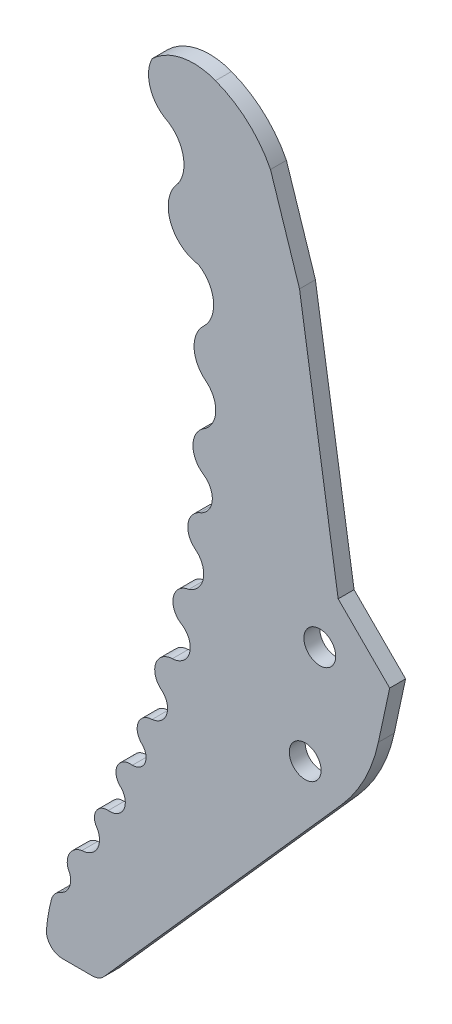
SolidWorks part; units mm, degrees
ref_plane "Front Plane" through (0, 0, 0) normal (0, 0, 1) x (1, 0, 0)
ref_plane "Top Plane" through (0, 0, 0) normal (0, 1, 0) x (1, 0, 0)
ref_plane "Right Plane" through (0, 0, 0) normal (1, 0, 0) x (0, 0, -1)
sketch "Sketch1" plane through (0, 0, 0) normal (0, 0, 1) x (1, 0, 0)
  line L0 (10.1218, 0) -> (2.5, 0) construction
  line L16 (5.147, -5.6126) -> (7.4417, -13.2)
  line L17 (16.8006, -3.4123) -> (24.6469, -23.8519)
  line L18 (25.0875, -29.5388) -> (22.1552, -43.1693)
  line L19 (19.858, -47.7041) -> (4.914, -64.542)
  line L20 (4.1661, -64.8782) -> (2.2859, -64.8782)
  line L21 (2.6676, 0.8279) -> (1.1408, 1.0183)
  line L22 (2.5, 0) -> (1.25, 0) construction
  line L26 (10.1218, 0) -> (-0.1303, -1.4408) construction
  line L27 (2.7011, -1.0876) -> (1.1818, -1.3311)
  line L28 (3.2523, -3.0101) -> (1.8349, -3.6086)
  line L34 (15.628, -20.9466) -> (13.7664, -16.0577) construction
  line L35 (14.5003, -21.376) -> (12.6387, -16.4871)
  line L36 (16.7556, -20.5172) -> (14.8941, -15.6283)
  line L37 (22.6069, -26.4997) -> (42.7977, -26.4997) construction
  line L38 (17.5548, -46.4997) -> (44.5231, -46.4997) construction
  line L41 (1.25, -4.8178) -> (1.25, -68.9399) construction
  line L42 (3.1515, 2.7685) -> (1.714, 3.3172)
  line L43 (4.0802, 4.4441) -> (2.8532, 5.3724)
  line L44 (5.4696, 5.8828) -> (4.499, 7.0767)
  line L45 (7.1117, 6.8695) -> (6.5132, 8.2869)
  line L46 (9.0342, 7.4207) -> (8.7907, 8.94)
  line L47 (10.9497, 7.4542) -> (11.1401, 8.981)
  line L48 (12.8903, 6.9703) -> (13.439, 8.4078)
  line L49 (14.5659, 6.0415) -> (15.4942, 7.2686)
  line L50 (16.0045, 4.6522) -> (17.1984, 5.6228)
  line L51 (16.9912, 3.0101) -> (18.4087, 3.6086)
  line L52 (17.5425, 1.0876) -> (19.0617, 1.3311)
  line L53 (17.5759, -0.8279) -> (19.1027, -1.0183)
  line L54 (17.0921, -2.7685) -> (18.5296, -3.3172)
  line L63 (4.239, -4.6522) -> (3.0451, -5.6228) [skipped]
  line L64 (5.6777, -6.0415) -> (5.3912, -6.4202) [skipped]
  line L65 (7.3533, -6.9703) -> (6.8046, -8.4078) [skipped]
  line L66 (9.2939, -7.4542) -> (9.1035, -8.981) [skipped]
  line L67 (11.2093, -7.4207) -> (11.4529, -8.94) [skipped]
  line L68 (13.6719, -8.1484) -> (13.7304, -8.2869) [skipped]
  line L69 (14.774, -5.8828) -> (15.6913, -7.0112) [skipped]
  line L70 (16.1633, -4.4441) -> (17.3904, -5.3724) [skipped]
  arc A13 (7.1115, -14.2685) -> (9.6978, -21.1131) centre (9.5249, -17.2675) ccw
  arc A16 (1.1818, -1.3311) -> (1.8349, -3.6086) centre (1.5311, -2.4634) ccw
  arc A23 (10.7326, -21.97) -> (10.8477, -22.8183) centre (-44.6411, -29.9177) cw
  arc A24 (1.6015, -62) -> (1.2897, -63.791) centre (11.9543, -64.725) ccw
  arc A25 (4.914, -64.542) -> (4.1661, -64.8782) centre (4.1661, -63.8782) cw
  arc A26 (2.2859, -64.8782) -> (1.2897, -63.791) centre (2.2859, -63.8782) cw
  arc A27 (22.1552, -43.1693) -> (19.858, -47.7041) centre (12.3789, -41.0662) cw
  arc A28 (24.6469, -23.8519) -> (25.0875, -29.5388) centre (15.3111, -27.4357) cw
  circle A30 centre (10.1218, 0) radius 1
  circle A31 centre (15.628, -9.2603) radius 2.25
  circle A32 centre (9.1218, -17.5263) radius 0.9981
  arc A33 (14.5003, -21.376) -> (16.7556, -20.5172) centre (15.628, -20.9466) ccw
  arc A34 (14.8941, -15.6283) -> (12.6387, -16.4871) centre (13.7664, -16.0577) ccw
  circle A35 centre (22.6069, -26.4997) radius 1
  circle A36 centre (22.6069, -33.1664) radius 1
  circle A37 centre (18.4742, -39.833) radius 1
  circle A38 centre (17.5548, -46.4997) radius 1
  arc A39 (3.5195, -58.3776) -> (4.478, -56.6894) centre (3.4947, -57.2474) ccw
  arc A40 (4.478, -56.6894) -> (5.1728, -55.3731) centre (5.1184, -56.1859) cw
  arc A41 (5.1728, -55.3731) -> (5.9791, -53.7296) centre (5.2695, -54.401) ccw
  arc A42 (5.9791, -53.7296) -> (6.6933, -52.1481) centre (6.5575, -53.0388) cw
  arc A43 (6.6933, -52.1481) -> (7.2971, -50.6981) centre (6.7052, -51.3023) ccw
  arc A44 (7.2971, -50.6981) -> (7.932, -49.0351) centre (7.9512, -49.9951) cw
  arc A45 (7.932, -49.0351) -> (8.5712, -47.1764) centre (7.8216, -47.9579) ccw
  arc A46 (8.5712, -47.1764) -> (9.2023, -45.0931) centre (9.247, -46.2439) cw
  arc A47 (9.2023, -45.0931) -> (9.7684, -42.9183) centre (9.1568, -43.9202) ccw
  arc A48 (9.7684, -42.9183) -> (10.2303, -40.8052) centre (10.39, -41.9471) cw
  arc A49 (10.2303, -40.8052) -> (10.6508, -38.4154) centre (9.7964, -39.497) ccw
  arc A50 (10.6508, -38.4154) -> (10.9372, -36.2787) centre (11.4277, -37.432) cw
  arc A51 (10.9372, -36.2787) -> (11.1453, -34.0756) centre (10.4704, -35.1232) ccw
  arc A52 (11.1453, -34.0756) -> (11.277, -31.5211) centre (12.0035, -32.8392) cw
  arc A53 (11.277, -31.5211) -> (11.2908, -28.902) centre (10.2837, -30.2063) ccw
  arc A54 (11.2908, -28.902) -> (11.1632, -26.0077) centre (12.4931, -27.399) cw
  arc A55 (11.1632, -26.0077) -> (10.8477, -22.8183) centre (9.7776, -24.5344) ccw
  arc A57 (9.6978, -21.1131) -> (10.7326, -21.97) centre (9.7427, -22.112) cw
  arc A58 (7.4417, -13.2) -> (7.1115, -14.2685) centre (6.4845, -13.4895) cw
  arc A59 (3.5195, -58.3776) -> (2.639, -59.7833) centre (3.7042, -59.4719) ccw
  arc A60 (2.639, -59.7833) -> (2.1678, -61.3383) centre (1.7398, -60.3597) cw
  arc A61 (2.1678, -61.3383) -> (1.6015, -62) centre (2.5686, -62.2545) ccw
  arc A70 (16.8006, -3.4123) -> (17.0921, -2.7685) centre (10.1218, 0) ccw
  arc A71 (1.714, 3.3172) -> (1.1408, 1.0183) centre (1.4503, 2.162) ccw
  arc A72 (4.499, 7.0767) -> (2.8532, 5.3724) centre (3.6931, 6.2081) ccw
  arc A73 (8.7907, 8.94) -> (6.5132, 8.2869) centre (7.6584, 8.5907) ccw
  arc A74 (13.439, 8.4078) -> (11.1401, 8.981) centre (12.2838, 8.6715) ccw
  arc A76 (2.6948, -1.0438) -> (2.7011, -1.0876) centre (10.1218, 0) ccw
  arc A78 (17.1984, 5.6228) -> (15.4942, 7.2686) centre (16.3299, 6.4287) ccw
  arc A79 (19.0617, 1.3311) -> (18.4087, 3.6086) centre (18.7125, 2.4634) ccw
  arc A80 (18.5296, -3.3172) -> (19.1027, -1.0183) centre (18.7932, -2.162) ccw
  arc A81 (3.2523, -3.0101) -> (5.147, -5.6126) centre (10.1218, 0) ccw
  arc A82 (17.5759, -0.8279) -> (17.5425, 1.0876) centre (10.1218, 0) ccw
  arc A83 (16.9912, 3.0101) -> (16.0045, 4.6522) centre (10.1218, 0) ccw
  arc A84 (14.5659, 6.0415) -> (12.8903, 6.9703) centre (10.1218, 0) ccw
  arc A85 (3.0451, -5.6228) -> (4.7494, -7.2686) centre (3.9137, -6.4287) ccw [skipped]
  arc A86 (6.8046, -8.4078) -> (9.1035, -8.981) centre (7.9597, -8.6715) ccw [skipped]
  arc A87 (13.3871, -9.4629) -> (13.7304, -8.2869) centre (12.5851, -8.5907) ccw [skipped]
  arc A88 (16.8314, -7.3592) -> (17.3904, -5.3724) centre (16.5505, -6.2081) ccw [skipped]
  arc A89 (10.9497, 7.4542) -> (9.0342, 7.4207) centre (10.1218, 0) ccw
  arc A90 (4.0802, 4.4441) -> (3.1515, 2.7685) centre (10.1218, 0) ccw
  arc A91 (7.1117, 6.8695) -> (5.4696, 5.8828) centre (10.1218, 0) ccw
  arc A92 (2.6676, 0.8279) -> (2.7011, -1.0876) centre (10.1218, 0) ccw
  point P59 (1.25, -64.8782)
  point P68 (10.1218, 0)
  point P88 (10.1218, 0)
  point P90 (10.1218, 0)
  point P105 (14.6972, -18.5021)
  point P119 (11.1632, -26.0077)
  point P122 (11.2908, -28.902)
  point P123 (11.277, -31.5211)
  point P124 (11.1453, -34.0756)
  point P125 (10.9372, -36.2787)
  point P126 (10.6508, -38.4154)
  point P127 (10.8477, -22.8183)
  point P128 (10.2303, -40.8052)
  point P129 (9.7684, -42.9183)
  point P130 (9.2023, -45.0931)
  point P131 (8.5712, -47.1764)
  point P132 (7.932, -49.0351)
  point P133 (7.2971, -50.6981)
  point P134 (6.6933, -52.1481)
  point P135 (5.9791, -53.7296)
  point P136 (5.1728, -55.3731)
  point P137 (4.478, -56.6894)
  point P138 (3.5195, -58.3776)
  dimension "D2" = 15
  dimension "D6" = 1
  dimension "D7" = 10
  dimension "D8" = 2
  dimension "D9" = 4.5
  dimension "D10" = 1.9961
  dimension "D12" = 2
  dimension "D15" = 1
  dimension "D16" = 1
  dimension "D3" = 12
  dimension "D11" = 20
  dimension "D13" = 6.6667
  dimension "D14" = 6.6667
  dimension "D17" = 8
extrude "Boss-Extrude2" add sketch "Sketch1" along normal blind 1 contours L21 A92 A76 L27 A16 L28 A81 L16 A58 A13 A57 A23 A55 A54 A53 A52 A51 A50 A49 A48 A47 A46 A45 A44 A43 A42 A41 A40 A39 A59 A60 A61 A24 A26 L20 A25 L19 A27 L18 A28 L17 A70 L54 A80 L53 A82 L52 A79 L51 A83 L50
sketch "Sketch2" plane through (0, 0, 1) normal (0, 0, 1) x (1, 0, 0)
  line L0 (23.0674, -38.9291) -> (13.378, -9.2603)
  line L1 (25.0875, -29.5388) -> (22.1552, -43.1693) construction
  line L2 (13.378, -9.2603) -> (6.2943, -9.4063)
  line L3 (5.147, -5.6126) -> (7.4417, -13.2) construction
  line L4 (6.2943, -9.4063) -> (-11.9745, 6.4191)
  line L5 (-11.9745, 6.4191) -> (6.2943, 12.783)
  line L6 (6.2943, 12.783) -> (25.9409, 9.601)
  line L7 (25.9409, 9.601) -> (30.0431, -7.3625)
  line L8 (30.0431, -7.3625) -> (32.8289, -29.9251)
  line L9 (32.8289, -29.9251) -> (23.0674, -38.9291)
  circle A0 centre (15.628, -9.2603) radius 2.25 construction
extrude "Cut-Extrude1" cut sketch "Sketch2" against normal through all both and the other way through all
sketch "Sketch3" plane through (0, 0, 1) normal (0, 0, 1) x (1, 0, 0)
  line L0 (16.7556, -20.5172) -> (14.8941, -15.6283) construction
  line L1 (14.5003, -21.376) -> (12.6387, -16.4871) construction
  line L2 (16.7556, -20.5172) -> (14.8941, -15.6283)
  line L3 (14.5003, -21.376) -> (12.6387, -16.4871)
  circle A0 centre (9.1218, -17.5263) radius 0.9981 construction
  arc A1 (14.5003, -21.376) -> (16.7556, -20.5172) centre (15.628, -20.9466) ccw construction
  arc A2 (14.8941, -15.6283) -> (12.6387, -16.4871) centre (13.7664, -16.0577) ccw construction
  circle A3 centre (9.1218, -17.5263) radius 0.9981
  arc A4 (14.5003, -21.376) -> (16.7556, -20.5172) centre (15.628, -20.9466) ccw
  arc A5 (14.8941, -15.6283) -> (12.6387, -16.4871) centre (13.7664, -16.0577) ccw
extrude "Boss-Extrude3" add sketch "Sketch3" against normal up to surface (1 mm away) up to face at (10.1199, -17.5263, 0)
sketch "Sketch4" plane through (0, 0, 1) normal (0, 0, 1) x (1, 0, 0)
  line L0 (13.8117, -10.5883) -> (23.0674, -38.9291) construction
  line L1 (10.8477, -22.8183) -> (15.374, -15.3722)
  arc A0 (10.8477, -22.8183) -> (9.5833, -19.0178) centre (11.2, -20.5905) cw
  arc A1 (9.5833, -19.0178) -> (8.9445, -15.9997) centre (7.7549, -17.8281) ccw
  arc A2 (8.9445, -15.9997) -> (7.9236, -13.0684) centre (9.8997, -14.0236) cw
  arc A3 (7.9236, -13.0684) -> (11.9176, -12.2648) centre (10.5443, -15.7662) cw
  arc A4 (11.9176, -12.2648) -> (15.374, -15.3722) centre (9.6739, -18.2365) cw
extrude "Boss-Extrude4" add sketch "Sketch4" against normal blind 1.1
sketch "Sketch5" plane through (0, 0, 0) normal (0, 0, -1) x (-1, 0, 0)
  line L3 (-7.4417, -13.2) -> (-6.2943, -9.4063)
  line L4 (-6.2943, -9.4063) -> (-13.378, -9.2603)
  line L5 (-13.8117, -10.5883) -> (-15.374, -15.3722)
  line L6 (-7.4417, -13.2) -> (-6.2943, -9.4063)
  line L7 (-6.2943, -9.4063) -> (-13.378, -9.2603)
  line L8 (-13.8117, -10.5883) -> (-15.374, -15.3722)
  arc A8 (-8.9445, -15.9997) -> (-9.5833, -19.0178) centre (-7.7549, -17.8281) ccw
  arc A10 (-8.9985, -21.0808) -> (-7.1115, -14.2685) centre (-9.5249, -17.2675) ccw
  arc A11 (-7.4417, -13.2) -> (-7.1115, -14.2685) centre (-6.4845, -13.4895) ccw
  arc A12 (-13.8117, -10.5883) -> (-13.378, -9.2603) centre (-15.628, -9.2603) ccw
  arc A13 (-8.9445, -15.9997) -> (-9.5833, -19.0178) centre (-7.7549, -17.8281) ccw
  arc A15 (-8.9985, -21.0808) -> (-9.5833, -19.0178) centre (-11.2, -20.5905) ccw
  arc A18 (-8.9985, -21.0808) -> (-7.1115, -14.2685) centre (-9.5249, -17.2675) ccw
  arc A19 (-7.4417, -13.2) -> (-7.1115, -14.2685) centre (-6.4845, -13.4895) ccw
  arc A20 (-13.8117, -10.5883) -> (-13.378, -9.2603) centre (-15.628, -9.2603) ccw
  arc A24 (-8.9985, -21.0808) -> (-9.5833, -19.0178) centre (-11.2, -20.5905) ccw
  arc A25 (-11.9176, -12.2648) -> (-15.374, -15.3722) centre (-9.6739, -18.2365) ccw
  arc A26 (-11.9176, -12.2648) -> (-15.374, -15.3722) centre (-9.6739, -18.2365) ccw
  arc A27 (-7.9236, -13.0684) -> (-11.9176, -12.2648) centre (-10.5443, -15.7662) ccw
  arc A28 (-7.9236, -13.0684) -> (-11.9176, -12.2648) centre (-10.5443, -15.7662) ccw
  arc A29 (-8.9445, -15.9997) -> (-7.9236, -13.0684) centre (-9.8997, -14.0236) ccw
  arc A30 (-8.9445, -15.9997) -> (-7.9236, -13.0684) centre (-9.8997, -14.0236) ccw
  dimension "D1" = 0
extrude "Cut-Extrude2" cut sketch "Sketch5" against normal through all both and the other way through all
sketch "Sketch6" plane through (9.3558, 3.0555, 0) normal (0.9506, 0.3104, 0) x (0, 0, -1)
  line L0 (0, -25.0585) -> (0.3743, -25.0205)
  line L1 (0.3743, -25.0205) -> (2.9265, -10.6962)
  line L2 (2.9265, -10.6962) -> (0, -13.4964)
  line L3 (0, -13.4964) -> (0, -25.0585)
extrude "Cut-Extrude3" cut sketch "Sketch6" against normal through all both and the other way through all
sketch "Sketch7" plane through (0, 0, 0) normal (0, 0, -1) x (-1, 0, 0)
  line L0 (-22.8674, -39.8588) -> (-19.6293, -36.6207)
  line L1 (-23.0674, -38.9291) -> (-22.1552, -43.1693) construction
  line L2 (-19.6293, -36.6207) -> (-17.1986, -20.9589)
  line L3 (-15.374, -15.3722) -> (-23.0674, -38.9291) construction
  line L4 (-17.1986, -20.9589) -> (-20.4664, -20.9589)
  line L5 (-20.4664, -20.9589) -> (-26.546, -37.4474)
  line L6 (-26.546, -37.4474) -> (-22.8674, -39.8588)
extrude "Cut-Extrude4" cut sketch "Sketch7" against normal through all both and the other way through all
